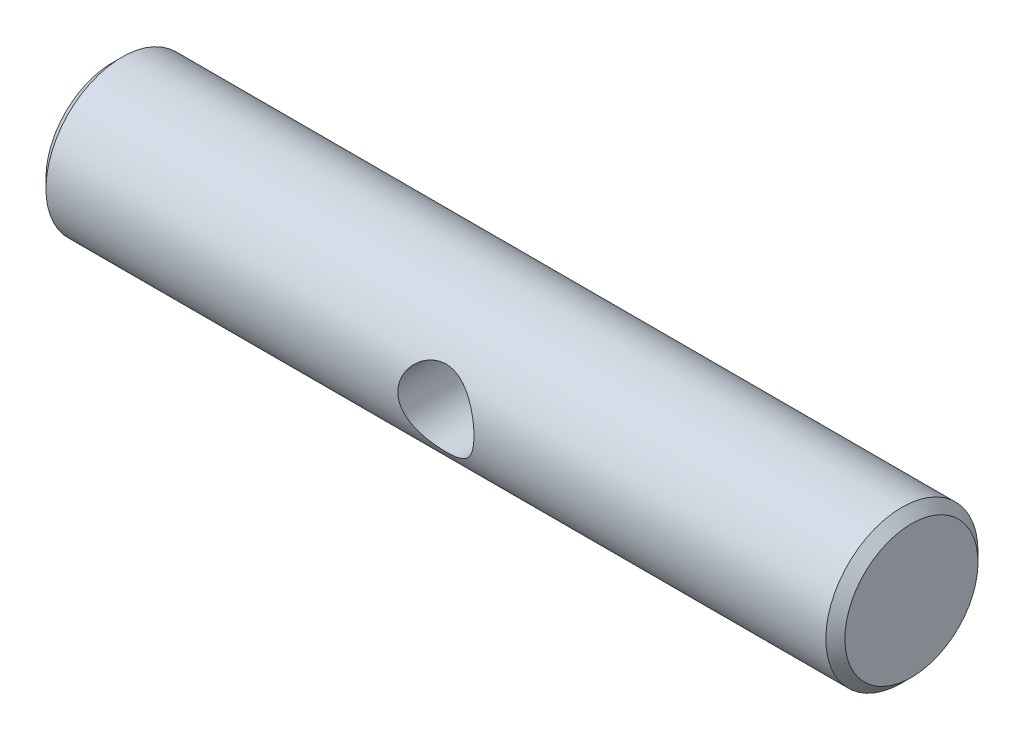
SolidWorks part; units mm, degrees
ref_plane "前视基准面" through (0, 0, 0) normal (0, 0, 1) x (1, 0, 0)
ref_plane "上视基准面" through (0, 0, 0) normal (0, 1, 0) x (1, 0, 0)
ref_plane "右视基准面" through (0, 0, 0) normal (1, 0, 0) x (0, 0, -1)
sketch "草图1" plane through (0, 0, 0) normal (0, 0, 1) x (1, 0, 0)
  line L0 (-16.7018, 0) -> (17, 0)
  line L1 (0, 0) -> (0, 2)
  line L2 (0, 2) -> (4, 2)
  line L3 (4, 2) -> (4, 4)
  line L4 (4, 4) -> (17, 4)
  line L5 (17, 4) -> (17, 2)
  line L6 (17, 2) -> (21, 2)
  line L7 (21, 2) -> (21, 0)
  line L8 (21, 0) -> (17, 0)
  dimension "D1" = 2
  dimension "D2" = 2
  dimension "D3" = 4
  dimension "D4" = 13
  dimension "D5" = 4
  dimension "D6" = 4
revolve "旋转2" add sketch "草图1" angle 360 about L0
sketch "草图2" plane through (0, 0, 0) normal (0, 0, 1) x (1, 0, 0)
  line L0 (17, 4) -> (4, 4)
  line L1 (12.5, -5.8272) -> (8.5, -5.8272)
  line L2 (12.5, -5.8272) -> (12.5, 5.8272)
  line L3 (12.5, 5.8272) -> (8.5, 5.8272)
  line L4 (8.5, -5.8272) -> (8.5, 5.8272)
  line L6 (12.5, 5.8272) -> (11.8729, 4) construction
  line L7 (17, 4) -> (4, 4) construction
  line L8 (10.5, 4) -> (10.5, 4.8104)
  line L9 (9.1271, 4) -> (8.5, 5.8272) construction
  dimension "D2" = 4
  dimension "D3" = 2
extrude "切除-拉伸1" cut sketch "草图2" against normal blind 10 from offset 3.5 contours L4 L1 L2 L0 offset against normal yes
sketch "草图3" plane through (0, 0, 0) normal (0, 1, 0) x (1, 0, 0)
  line L0 (8.5, 3.5) -> (12.5, 3.5) construction
  line L1 (12.5, 13.3353) -> (8.5, 13.3353)
  line L2 (12.5, 13.3353) -> (12.5, -6.3353)
  line L3 (12.5, -6.3353) -> (8.5, -6.3353)
  line L4 (8.5, 13.3353) -> (8.5, -6.3353)
  line L5 (12.5, 13.3353) -> (8.5, -6.3353) construction
  line L6 (12.5, -6.3353) -> (8.5, 13.3353) construction
  point P0 (10.5, 3.5)
  dimension "D1" = 4
extrude "切除-拉伸2" cut sketch "草图3" against normal blind 10 from offset 3.5 offset against normal yes
sketch "草图4" plane through (21, 0, 0) normal (1, 0, 0) x (0, 0, -1)
  circle A1 centre (0, 0) radius 2
  circle A2 centre (0, 0) radius 2
  circle A3 centre (0, 0) radius 4
  circle A4 centre (0, 0) radius 4
  dimension "D1" = 0
  dimension "D2" = 0
extrude "切除-拉伸3" cut sketch "草图4" against normal blind 29
sketch "草图5" plane through (0, 0, 0) normal (0, 0, 1) x (1, 0, 0)
  circle A0 centre (10.5, 0) radius 1
  dimension "D1" = 2
extrude "切除-拉伸4" cut sketch "草图5" against normal mid plane 10
chamfer "倒角1" distance 0.25 2 edges at (0, -2, 0) (21, -2, 0)
